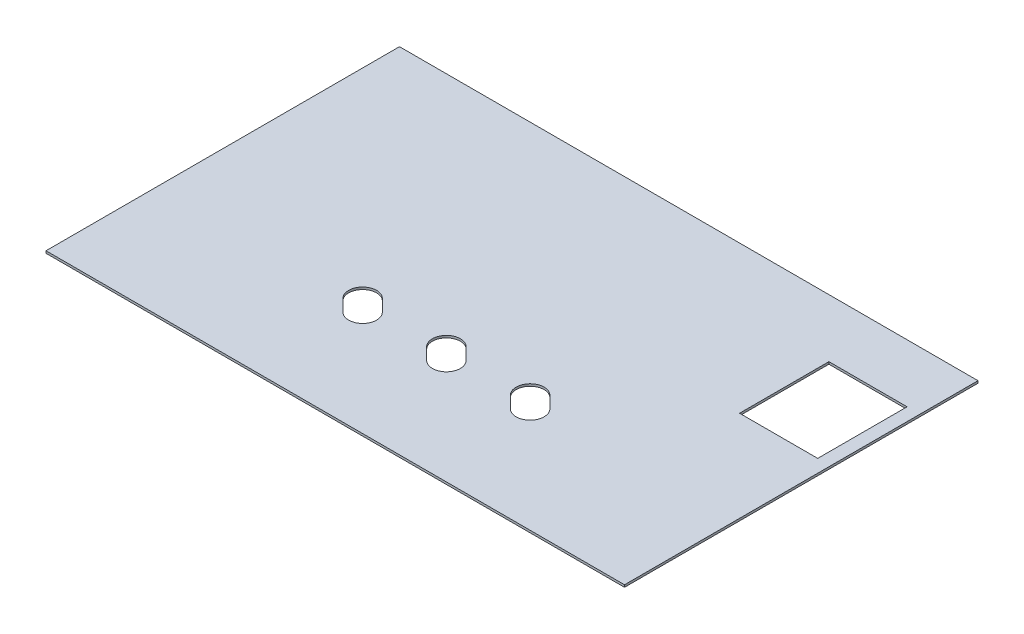
SolidWorks part; units mm, degrees
material "PET"
ref_plane "Front Plane" through (0, 0, 0) normal (0, 0, 1) x (1, 0, 0)
ref_plane "Top Plane" through (0, 0, 0) normal (0, 1, 0) x (1, 0, 0)
ref_plane "Right Plane" through (0, 0, 0) normal (1, 0, 0) x (0, 0, -1)
sketch "Sketch1" plane through (0, 0, 0) normal (0, 1, 0) x (1, 0, 0)
  line L1 (-51.8, 31.65) -> (51.8, 31.65)
  line L2 (-51.8, 31.65) -> (-51.8, -31.65)
  line L3 (-51.8, -31.65) -> (51.8, -31.65)
  line L4 (51.8, 31.65) -> (51.8, -31.65)
  line L5 (-51.8, 31.65) -> (51.8, -31.65) construction
  line L6 (-51.8, -31.65) -> (51.8, 31.65) construction
  point P0 (0, 0)
  dimension "D1" = 63.3
  dimension "D2" = 103.6
extrude "Boss-Extrude1" add sketch "Sketch1" against normal blind 0.4
sketch "Sketch2" plane through (0, 0, 0) normal (0, 1, 0) x (1, 0, 0)
  line L4 (49.5, 5.25) -> (35.5, 5.25)
  line L5 (49.5, 21.25) -> (49.5, 5.25)
  line L6 (35.5, 21.25) -> (49.5, 21.25)
  line L7 (35.5, 5.25) -> (35.5, 21.25)
  line L9 (51.8, -31.65) -> (51.8, 31.65) construction
  line L10 (51.8, 31.65) -> (-51.8, 31.65) construction
  dimension "D1" = 16
  dimension "D2" = 14
  dimension "D3" = 2.3
  dimension "D4" = 10.4
sketch "Sketch3" plane through (0, 0, 0) normal (0, 1, 0) x (1, 0, 0)
  line L0 (-1.0607, -10.6893) -> (1.0607, -12.8107) construction
  line L1 (0.7071, -8.9216) -> (2.8284, -11.0429)
  line L4 (-51.8, -31.65) -> (51.8, -31.65) construction
  line L12 (-2.8284, -12.4571) -> (-0.7071, -14.5784)
  line L13 (0, -11.75) -> (0, 0) construction
  arc A0 (0.7071, -8.9216) -> (-2.8284, -12.4571) centre (-1.0607, -10.6893) ccw
  arc A1 (-0.7071, -14.5784) -> (2.8284, -11.0429) centre (1.0607, -12.8107) ccw
  point P6 (0, -11.75)
  dimension "D4" = 2.5
  dimension "D2" = 45
  dimension "D3" = 3
  dimension "D1" = 19.9
extrude "Cut-Extrude1" cut sketch "Sketch2" against normal through all
extrude "Cut-Extrude2" cut sketch "Sketch3" against normal through all
pattern_linear "LPattern1" count 2 spacing 15 along (1, 0, 0) count 2 spacing 15 along (-1, 0, 0) of "Cut-Extrude2"
